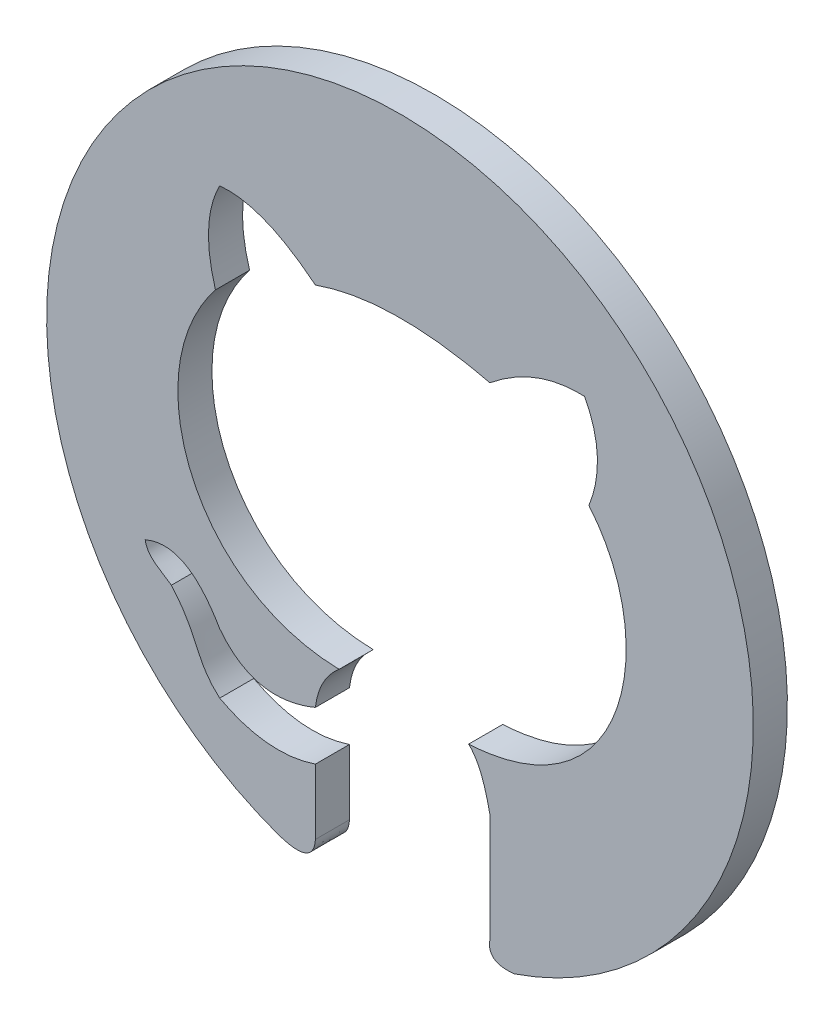
SolidWorks part; units mm, degrees
ref_plane "Plano frontal" through (0, 0, 0) normal (0, 0, 1) x (1, 0, 0)
ref_plane "Plano superior" through (0, 0, 0) normal (0, 1, 0) x (1, 0, 0)
ref_plane "Plano direito" through (0, 0, 0) normal (1, 0, 0) x (0, 0, -1)
sketch "Esboço1" plane through (0, 0, 0) normal (0, 0, 1) x (1, 0, 0)
  line L0 (-7.2326, -62.4843) -> (-7.2326, -94.5339)
  line L1 (-58.4126, -75.4035) -> (-58.4126, -94.5339)
  arc A0 (0, -99.5028) -> (-69.0379, -98.8466) centre (-33.5899, -1.4268) ccw
  spline S0 degree 2 poles (-58.4126, 46.3353) (-73.7579, 58.7572) (-86.4871, 57.5154) knots 0 0 0 1 1 1
  spline S1 degree 2 poles (-86.4871, 57.5154) (-92.3845, 46.0309) (-87.7293, 30.4347) knots 0 0 0 1 1 1
  spline S2 degree 2 poles (-58.4126, 46.3353) (-36.3647, 54.0986) (-7.2326, 47.0806) knots 0 0 0 1 1 1
  spline S3 degree 2 poles (-7.2326, 47.0806) (6.3077, 58.1365) (20.5934, 57.5154) knots 0 0 0 1 1 1
  spline S4 degree 2 poles (20.5934, 57.5154) (27.4214, 44.3992) (21.8356, 30.4347) knots 0 0 0 1 1 1
  spline S5 degree 3 poles (21.8356, 30.4347) (43.5743, 4.9694) (33.4494, -45.3415) (-13.4438, -47.8259) knots 0 0 0 0 1 1 1 1
  spline S6 degree 3 poles (-13.4438, -47.8259) (-10.1377, -50.9255) (-8.4748, -56.584) (-7.2326, -62.4843) knots 0 0 0 0 1 1 1 1
  spline S7 degree 2 poles (0, -99.5028) (-8.1593, -100.4026) (-7.2326, -94.5339) knots 0 0 0 1 1 1
  spline S8 degree 2 poles (-69.0379, -98.8466) (-58.8779, -102.1461) (-58.4126, -94.5339) knots 0 0 0 1 1 1
  spline S9 degree 3 poles (-87.7293, 30.4347) (-112.2619, -0.6192) (-93.9982, -46.8944) (-51.4561, -47.8259) knots 0 0 0 0 1 1 1 1
  spline S10 degree 2 poles (-51.4561, -47.8259) (-57.4818, -52.9268) (-58.4126, -60.9936) knots 0 0 0 1 1 1
  spline S11 degree 2 poles (-58.4126, -60.9936) (-76.2398, -68.3834) (-86.4871, -55.0309) knots 0 0 0 1 1 1
  spline S12 degree 2 poles (-86.4871, -55.0309) (-96.2392, -38.0747) (-108.3504, -43.3539) knots 0 0 0 1 1 1
  spline S13 degree 3 poles (-108.3504, -43.3539) (-107.7302, -46.868) (-104.9911, -48.2641) (-100.6485, -51.0558) knots 0 0 0 0 1 1 1 1
  spline S14 degree 3 poles (-100.6485, -51.0558) (-92.2646, -60.6818) (-93.9385, -66.1506) (-86.4871, -72.6706) knots 0 0 0 0 1 1 1 1
  spline S15 degree 2 poles (-86.4871, -72.6706) (-72.514, -80.1229) (-58.4126, -75.4035) knots 0 0 0 1 1 1
extrude "Ressalto-extrusão1" add sketch "Esboço1" along normal blind 10
